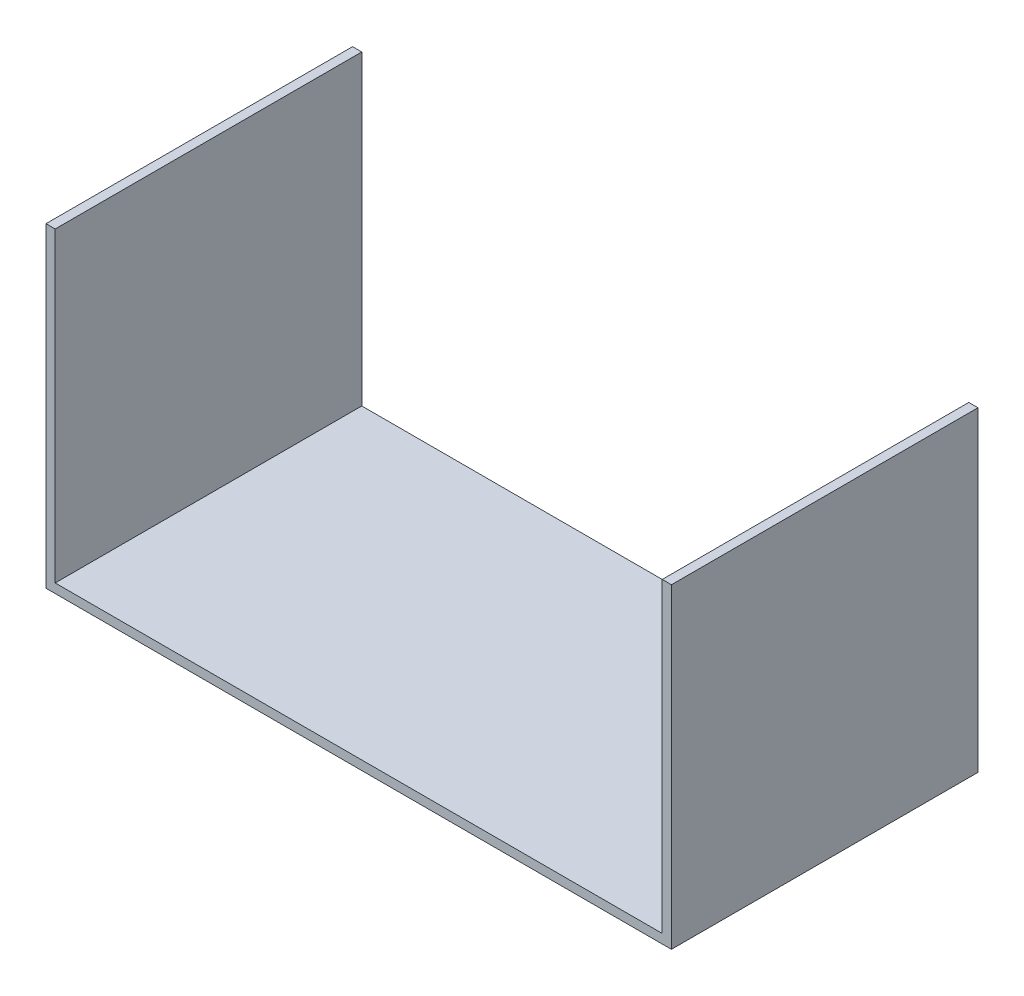
SolidWorks part; units mm, degrees
ref_plane "Front Plane" through (0, 0, 0) normal (0, 0, 1) x (1, 0, 0)
ref_plane "Top Plane" through (0, 0, 0) normal (0, 1, 0) x (1, 0, 0)
ref_plane "Right Plane" through (0, 0, 0) normal (1, 0, 0) x (0, 0, -1)
sketch "Sketch1" plane through (0, 0, 0) normal (0, 1, 0) x (1, 0, 0)
  line L1 (0, 0) -> (102, 0)
  line L2 (0, 0) -> (0, 50)
  line L3 (0, 50) -> (102, 50)
  line L4 (102, 0) -> (102, 50)
  dimension "D1" = 50
  dimension "D2" = 102
extrude "Boss-Extrude1" add sketch "Sketch1" along normal blind 1.5
sketch "Sketch2" plane through (0, 1.5, 0) normal (0, 1, 0) x (1, 0, 0)
  line L0 (102, 50) -> (0, 50) construction
  line L1 (0, 0) -> (1.5, 0)
  line L2 (0, 0) -> (0, 50)
  line L3 (0, 50) -> (1.5, 50)
  line L4 (1.5, 0) -> (1.5, 50)
  line L6 (102, 0) -> (100.5, 0)
  line L7 (102, 0) -> (102, 50)
  line L8 (102, 50) -> (100.5, 50)
  line L9 (100.5, 0) -> (100.5, 50)
  dimension "D1" = 1.5
  dimension "D2" = 1.5
extrude "Boss-Extrude2" add sketch "Sketch2" along normal blind 50
